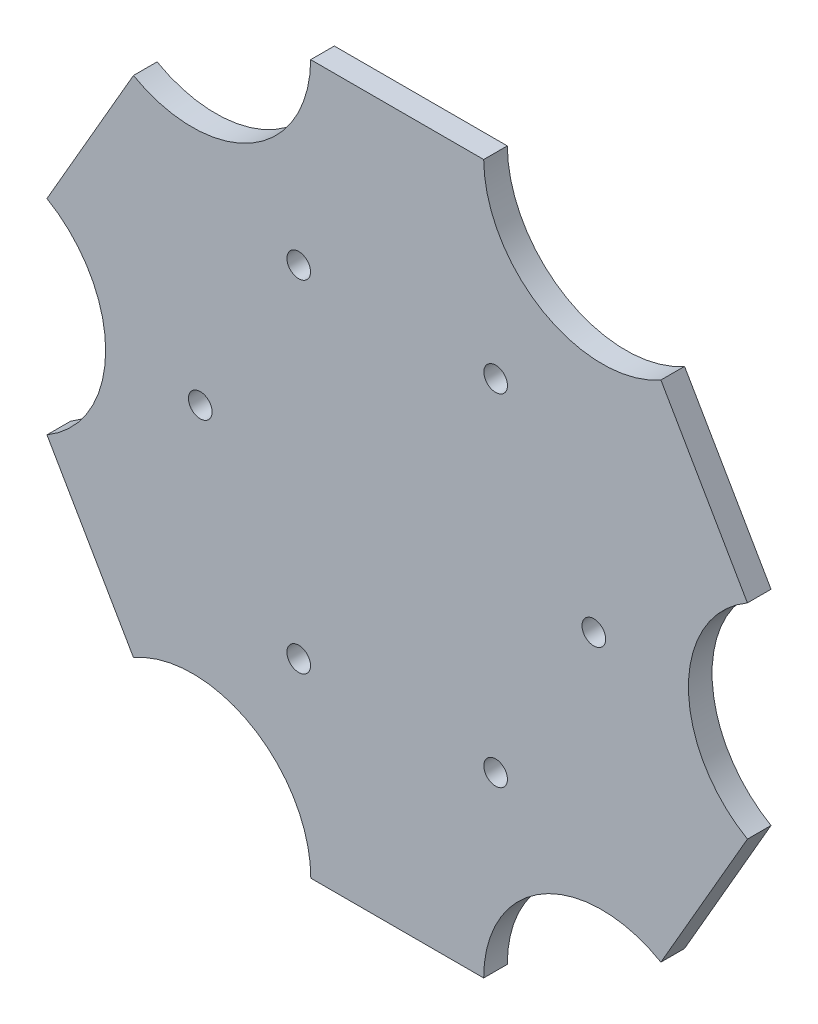
SolidWorks part; units mm, degrees
ref_plane "Front Plane" through (0, 0, 0) normal (0, 0, 1) x (1, 0, 0)
ref_plane "Top Plane" through (0, 0, 0) normal (0, 1, 0) x (1, 0, 0)
ref_plane "Right Plane" through (0, 0, 0) normal (1, 0, 0) x (0, 0, -1)
sketch "Sketch1" plane through (0, 0, 0) normal (0, 0, 1) x (1, 0, 0)
  line L0 (112.5374, -12.9761) -> (101.5567, -31.9954)
  line L1 (135.0374, 0.0142) -> (156.999, 0.0142)
  line L3 (179.499, -12.9761) -> (190.4797, -31.9954)
  line L5 (190.4797, -57.9642) -> (179.499, -76.9834)
  line L7 (156.999, -89.9738) -> (135.0514, -89.9738)
  line L9 (112.5436, -76.9799) -> (101.5567, -57.9761)
  arc A0 (112.5374, -12.9761) -> (135.0374, 0.0142) centre (119.9796, 0.1144) ccw
  arc A1 (156.999, 0.0142) -> (179.499, -12.9761) centre (172.0568, 0.1144) ccw
  arc A2 (190.4797, -31.9954) -> (190.4797, -57.9642) centre (197.9932, -44.9798) ccw
  arc A3 (101.5567, -31.9954) -> (101.5567, -57.9761) centre (93.9589, -44.9858) cw
  arc A4 (112.5436, -76.9799) -> (135.0514, -89.9738) centre (120.0514, -89.9657) cw
  arc A5 (156.999, -89.9738) -> (179.499, -76.9834) centre (171.9902, -89.9586) cw
  circle A6 centre (133.5174, -23.3338) radius 1.5
  circle A7 centre (158.519, -23.3338) radius 1.5
  circle A8 centre (170.9816, -44.9808) radius 1.5
  circle A9 centre (121.018, -44.9848) radius 1.5
  circle A10 centre (158.519, -66.6258) radius 1.5
  circle A11 centre (133.5174, -66.6258) radius 1.5
  point P28 (107.0471, -22.4858)
  point P46 (109.008, -44.9858)
extrude "Boss-Extrude2" add sketch "Sketch1" along normal blind 3
